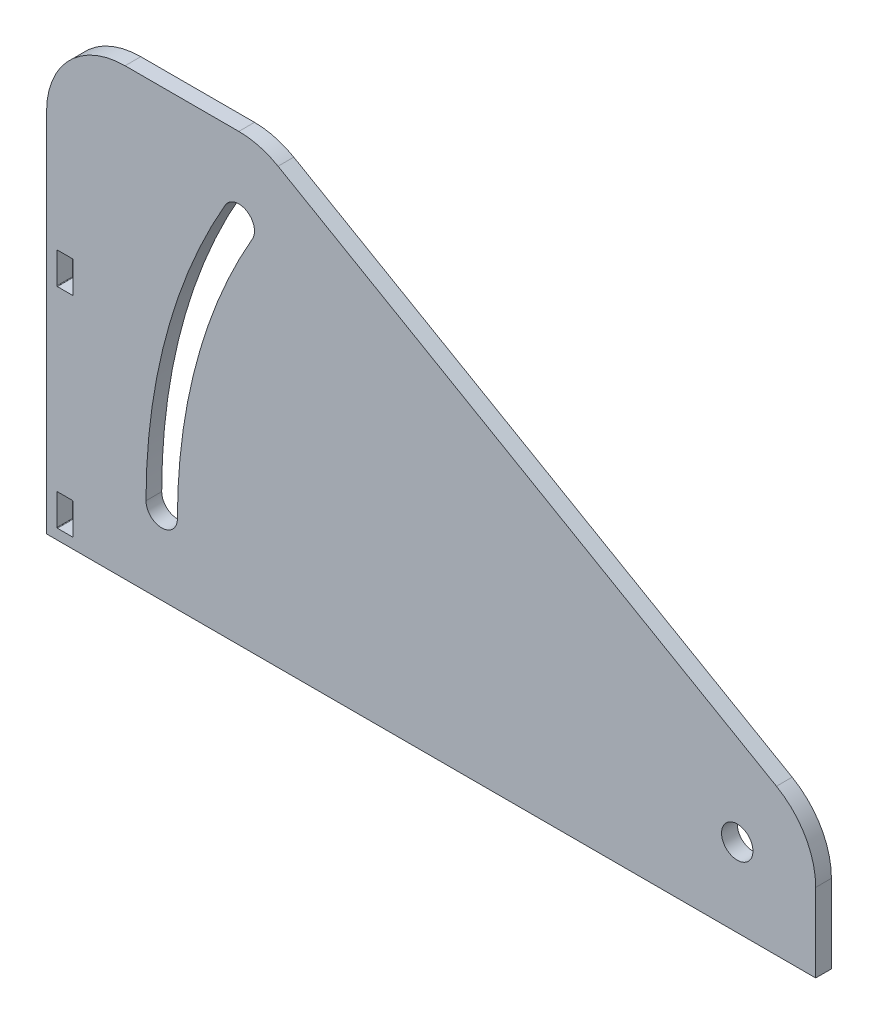
SolidWorks part; units mm, degrees
ref_plane "Front Plane" through (0, 0, 0) normal (0, 0, 1) x (1, 0, 0)
ref_plane "Top Plane" through (0, 0, 0) normal (0, 1, 0) x (1, 0, 0)
ref_plane "Right Plane" through (0, 0, 0) normal (1, 0, 0) x (0, 0, -1)
sketch "Sketch1" plane through (0, 0, 0) normal (0, 0, 1) x (1, 0, 0)
  line L0 (-73.5, -27.5) -> (73.5, -27.5) construction
  line L1 (-73.5, 42.5) -> (73.5, 42.5)
  line L2 (-73.5, 42.5) -> (-73.5, -42.5)
  line L3 (-73.5, -42.5) -> (73.5, -42.5)
  line L4 (73.5, 42.5) -> (73.5, -42.5)
  line L5 (-73.5, 42.5) -> (73.5, -42.5) construction
  line L6 (-73.5, -42.5) -> (73.5, 42.5) construction
  line L7 (58.5, -27.5) -> (-51.5, -27.5) construction
  line L8 (-73.5, 7.5) -> (-48.943, 7.5) construction
  line L9 (-36.7628, 27.5) -> (-36.7628, 42.5) construction
  line L10 (-36.7628, 27.5) -> (58.5, -27.5) construction
  line L11 (-51.5, -27.5) -> (-51.5, -42.5) construction
  line L12 (66, -14.5096) -> (-32.7436, 42.5)
  line L13 (-71.5, 5.5) -> (-68.5, 5.5)
  line L18 (-71.5, 5.5) -> (-71.5, -0.5)
  line L19 (-71.5, -0.5) -> (-68.5, -0.5)
  line L20 (-68.5, 5.5) -> (-68.5, -0.5)
  line L21 (-71.5, -34.5) -> (-68.5, -34.5)
  line L22 (-71.5, -34.5) -> (-71.5, -40.5)
  line L23 (-71.5, -40.5) -> (-68.5, -40.5)
  line L24 (-68.5, -34.5) -> (-68.5, -40.5)
  line L25 (-71.5, -40.5) -> (-71.5, -42.5) construction
  line L26 (-71.5, -0.5) -> (-73.5, -0.5) construction
  line L27 (-71.5, 5.5) -> (-71.5, 7.5) construction
  line L28 (-68.5, -0.5) -> (-71.5, 5.5) construction
  line L29 (-71.5, 5.5) -> (-71.525, 5.5) construction
  line L30 (-68.475, -0.525) -> (-71.525, -0.525)
  line L31 (-68.475, -0.525) -> (-68.475, 5.525)
  line L32 (-68.475, 5.525) -> (-71.525, 5.525)
  line L33 (-71.525, -0.525) -> (-71.525, 5.525)
  line L34 (-68.475, -0.525) -> (-71.525, 5.525) construction
  line L35 (-68.475, 5.525) -> (-71.525, -0.525) construction
  line L36 (-68.5, -0.5) -> (-68.5, -0.525) construction
  line L37 (-68.5, -40.5) -> (-71.5, -34.5) construction
  line L38 (-71.5, -34.5) -> (-71.525, -34.5) construction
  line L39 (-71.525, -40.525) -> (-68.475, -40.525)
  line L40 (-71.525, -40.525) -> (-71.525, -34.475)
  line L41 (-71.525, -34.475) -> (-68.475, -34.475)
  line L42 (-68.475, -40.525) -> (-68.475, -34.475)
  line L43 (-71.525, -40.525) -> (-68.475, -34.475) construction
  line L44 (-71.525, -34.475) -> (-68.475, -40.525) construction
  line L45 (-71.5, -34.5) -> (-71.5, -34.475) construction
  circle A0 centre (58.5, -27.5) radius 15
  circle A1 centre (58.5, -27.5) radius 3
  circle A2 centre (58.5, -27.5) radius 110
  circle A3 centre (-51.5, -27.5) radius 3
  circle A9 centre (-58.5, 27.5) radius 15
  circle A11 centre (-36.7628, 27.5) radius 3
  circle A12 centre (-51.1924, -19.2797) radius 3 [skipped]
  circle A13 centre (-50.2714, -11.1054) radius 3 [skipped]
  circle A14 centre (-48.7421, -3.0227) radius 3 [skipped]
  circle A15 centre (-46.613, 4.9231) radius 3 [skipped]
  circle A16 centre (-43.8961, 12.6875) radius 3 [skipped]
  circle A17 centre (-40.6066, 20.2272) radius 3 [skipped]
  circle A18 centre (58.5, -27.5) radius 113
  circle A19 centre (58.5, -27.5) radius 107
  point P0 (0, 0)
  point P27 (-70, 2.5)
  point P55 (-70, -37.5)
  dimension "D3" = 30
  dimension "D4" = 6
  dimension "D5" = 220
  dimension "D1" = 22
  dimension "D7" = 30
  dimension "D2" = 3
  dimension "D8" = 6
  dimension "D9" = 2
  dimension "D11" = 50
  dimension "D10" = 0.025
  dimension "D6" = 8
extrude "Boss-Extrude1" add sketch "Sketch1" along normal blind 3 contours A9 | A18 L12 L1 A9 L2 L3 L13 L20 L19 L18 L21 L24 L23 L22 | L12 A18 A11 A2 | A19 L12 A2 A11 | L12 A19 L3 A0 | A19 A3 A2 L3 | A3 A18 L3 A2 | A0 A1 | A0 L3 L4
fillet "Fillet1" radius 15 1 edges at (-32.7436, 42.5, 1.5)
fillet "Fillet2" radius 0.1 8 edges at (-68.475, -40.525, 1.5) (-68.475, -0.525, 1.5) (-68.475, -34.475, 1.5) (-68.475, 5.525, 1.5) (-71.525, 5.525, 1.5) (-71.525, -34.475, 1.5) (-71.525, -0.525, 1.5) (-71.525, -40.525, 1.5)
equation "\"D5@Sketch1\"=110*2"
equation "\"TOLERANCE\"= 0.025"
equation "\"D10@Sketch1\"=\"TOLERANCE\""
